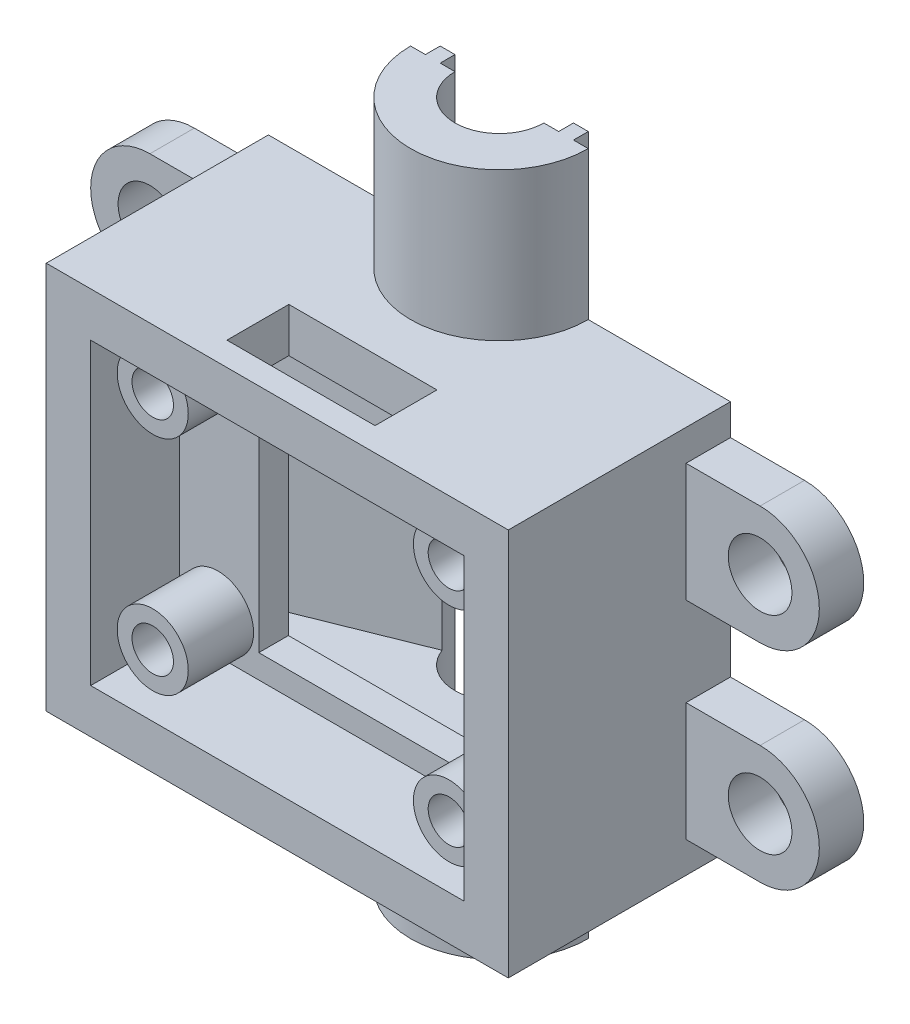
SolidWorks part; units mm, degrees
ref_plane "Front Plane" through (0, 0, 0) normal (0, 0, 1) x (1, 0, 0)
ref_plane "Top Plane" through (0, 0, 0) normal (0, 1, 0) x (1, 0, 0)
ref_plane "Right Plane" through (0, 0, 0) normal (1, 0, 0) x (0, 0, -1)
sketch "Sketch1" plane through (0, 0, 0) normal (0, 0, 1) x (1, 0, 0)
  line L1 (-15.6, -13.1) -> (15.6, -13.1)
  line L2 (-15.6, -13.1) -> (-15.6, 13.1)
  line L3 (-15.6, 13.1) -> (15.6, 13.1)
  line L4 (15.6, -13.1) -> (15.6, 13.1)
  line L5 (-15.6, -13.1) -> (15.6, 13.1) construction
  line L6 (-15.6, 13.1) -> (15.6, -13.1) construction
  point P0 (0, 0)
  dimension "D1" = 26.2
  dimension "D2" = 31.2
extrude "Boss-Extrude1" add sketch "Sketch1" along normal blind 15
shell "Shell2" thickness 3
sketch "Sketch3" plane through (0, 13.1, 0) normal (0, 1, 0) x (1, 0, 0)
  line L0 (15.6, 0) -> (-15.6, 0) construction
  line L1 (-6, 0) -> (-3, 0)
  line L2 (3, 0) -> (6, 0)
  arc A0 (-6, 0) -> (6, 0) centre (0, 0) ccw
  arc A1 (-3, 0) -> (3, 0) centre (0, 0) ccw
  dimension "D2" = 3
  dimension "D1" = 3
extrude "Boss-Extrude2" add sketch "Sketch3" along normal blind 10
ref_plane "Plane1" through (0, 0, 0) normal (0, 1, 0) x (1, 0, 0)
mirror "Mirror1" about plane through (0, 0, 0) normal (0, 1, 0) of "Boss-Extrude2"
sketch "Sketch4" plane through (0, 13.1, 0) normal (0, 1, 0) x (1, 0, 0)
  line L0 (3, 0) -> (-3, 0) construction
  line L1 (-3, 0) -> (3, 0)
  arc A0 (-3, 0) -> (3, 0) centre (0, 0) ccw
extrude "Cut-Extrude2" cut sketch "Sketch4" against normal through all
sketch "Sketch5" plane through (0, 13.1, 0) normal (0, 1, 0) x (1, 0, 0)
  line L1 (-5, -9.22) -> (5, -9.22)
  line L2 (-5, -9.22) -> (-5, -13.4)
  line L3 (-5, -13.4) -> (5, -13.4)
  line L4 (5, -9.22) -> (5, -13.4)
  line L5 (-5, -9.22) -> (5, -13.4) construction
  line L6 (-5, -13.4) -> (5, -9.22) construction
  line L9 (15.6, -15) -> (-15.6, -15) construction
  point P0 (0, -11.31)
  dimension "D1" = 10
  dimension "D3" = 4.18
  dimension "D4" = 1.6
sketch "Sketch8" plane through (0, 0, 0) normal (0, 0, -1) x (-1, 0, 0)
  line L0 (-15.6, 11) -> (-20.6, 11)
  line L1 (-15.6, -13.1) -> (-15.6, 13.1) construction
  line L2 (-15.6, 3) -> (-20.6, 3)
  line L3 (8.25, 0) -> (-8.25, 0) construction
  line L4 (-15.6, -3) -> (-20.6, -3)
  line L5 (-15.6, -11) -> (-20.6, -11)
  arc A0 (-20.6, 11) -> (-20.6, 3) centre (-20.6, 7) ccw
  circle A1 centre (-20.6, 7) radius 2.15
  circle A2 centre (-20.6, -7) radius 2.15
  arc A3 (-20.6, -11) -> (-20.6, -3) centre (-20.6, -7) cw
  line M9 (-15.6, 13.1) -> (-15.6, -13.1)
  dimension "D1" = 4.3
  dimension "D4" = 5
  dimension "D2" = 8
  dimension "D3" = 3
extrude "Boss-Extrude5" add sketch "Sketch8" against normal blind 3 contours L0 A0 L2 A1 M9 | A3 L5 L4 A2 M9
ref_plane "Plane3" through (0, 0, 0) normal (1, 0, 0) x (0, 0, -1)
mirror "Mirror3" about plane through (0, 0, 0) normal (1, 0, 0) of "Boss-Extrude5"
sketch "Sketch7" plane through (0, 0, 0) normal (0, 0, -1) x (-1, 0, 0)
  line L0 (-4.5, -23.1) -> (-4.5, -11.6) construction
  line L1 (-6, -23.1) -> (-3, -23.1) construction
  line L3 (-4.5, -11.6) -> (-14.1, -11.6) construction
  line L4 (-14.1, -11.6) -> (-14.1, 11.6) construction
  line L5 (-14.1, 11.6) -> (-4.5, 11.6) construction
  line L6 (-4.5, 11.6) -> (-4.5, 23.1) construction
  line L7 (-6, 23.1) -> (-3, 23.1) construction
  line L8 (-15.6, -13.1) -> (-15.6, -11) construction
  line L9 (-15.6, 13.1) -> (-6, 13.1) construction
  line L10 (-6, -13.1) -> (-15.6, -13.1) construction
  line L11 (-4, -23.1) -> (-4, -11.1)
  line L12 (-4, -11.1) -> (-13.6, -11.1)
  line L13 (-13.6, -11.1) -> (-13.6, 11.1)
  line L14 (-13.6, 11.1) -> (-4, 11.1)
  line L15 (-4, 11.1) -> (-4, 23.1)
  line L16 (-5, -23.1) -> (-5, -12.1)
  line L17 (-5, -12.1) -> (-14.6, -12.1)
  line L18 (-14.6, -12.1) -> (-14.6, 12.1)
  line L19 (-14.6, 12.1) -> (-5, 12.1)
  line L20 (-5, 12.1) -> (-5, 23.1)
  line L21 (-5, 23.1) -> (-4, 23.1)
  line L22 (-5, -23.1) -> (-4, -23.1)
  dimension "D1" = 1.5
  dimension "D2" = 1.5
  dimension "D3" = 1.5
  dimension "D4" = 0.5
  dimension "D5" = 0.5
extrude "Boss-Extrude4" add sketch "Sketch7" along normal blind 1
ref_plane "Plane2" through (0, 0, 0) normal (1, 0, 0) x (0, 0, -1)
mirror "Mirror2" about plane through (0, 0, 0) normal (1, 0, 0) of "Boss-Extrude4"
sketch "Sketch14" plane through (0, 0, 12) normal (0, 0, -1) x (-1, 0, 0)
  line L1 (-12.6, 10.1) -> (12.6, 10.1)
  line L2 (-12.6, 10.1) -> (-12.6, -10.1)
  line L3 (-12.6, -10.1) -> (12.6, -10.1)
  line L4 (12.6, 10.1) -> (12.6, -10.1)
  line L5 (-12.6, 10.1) -> (12.6, -10.1) construction
  line L6 (-12.6, -10.1) -> (12.6, 10.1) construction
  point P0 (0, 0)
extrude "Cut-Extrude5" cut sketch "Sketch14" against normal through all
sketch "Sketch11" plane through (0, -10.1, 0) normal (0, 1, 0) x (1, 0, 0)
  line L0 (3, 0) -> (12.6, 0)
  line L1 (3, 0) -> (12.6, 0) construction
  line L2 (12.6, 0) -> (12.6, -5.003)
  line L3 (12.6, -15) -> (12.6, 0) construction
  line L4 (12.6, -5.003) -> (2.8013, -1.0736)
  line L5 (0, -8.25) -> (0, 8.25) construction
  line L6 (-12.6, -5.003) -> (-2.8013, -1.0736)
  line L7 (-12.6, 0) -> (-12.6, -5.003)
  line L8 (-3, 0) -> (-12.6, 0)
  arc A0 (-3, 0) -> (3, 0) centre (0, 0) ccw construction
  arc A1 (2.8013, -1.0736) -> (3, 0) centre (0, 0) ccw
  arc A2 (-2.8013, -1.0736) -> (-3, 0) centre (0, 0) cw
extrude "Boss-Extrude8" add sketch "Sketch11" along normal up to next
sketch "Sketch15" plane through (0, 0, 15) normal (0, 0, 1) x (1, 0, 0)
  line L1 (-15.6, 13.1) -> (15.6, 13.1)
  line L2 (-15.6, 13.1) -> (-15.6, -13.1)
  line L3 (-15.6, -13.1) -> (15.6, -13.1)
  line L4 (15.6, 13.1) -> (15.6, -13.1)
  line L5 (-15.6, 13.1) -> (15.6, -13.1) construction
  line L6 (-15.6, -13.1) -> (15.6, 13.1) construction
  line L7 (-7.25, 8.5) -> (7.25, 8.5)
  line L8 (-7.25, 8.5) -> (-7.25, -8.5)
  line L9 (-7.25, -8.5) -> (7.25, -8.5)
  line L10 (7.25, 8.5) -> (7.25, -8.5)
  line L11 (-7.25, 8.5) -> (7.25, -8.5) construction
  line L12 (-7.25, -8.5) -> (7.25, 8.5) construction
  point P0 (0, 0)
  point P7 (0, 0)
  dimension "D1" = 14.5
  dimension "D2" = 17
extrude "Boss-Extrude9" add sketch "Sketch15" along normal blind 2 from offset 8 offset against normal yes
sketch "Sketch16" plane through (0, 0, 9) normal (0, 0, 1) x (1, 0, 0)
  line L1 (-12.6, 10.1) -> (-12.6, -10.1) construction
  line L5 (12.6, -10.1) -> (-12.6, -10.1) construction
  circle A0 centre (-10, 7.5) radius 2.4
  circle A1 centre (10, 7.5) radius 2.4
  circle A2 centre (-10, -7.5) radius 2.4
  circle A3 centre (10, -7.5) radius 2.4
  circle A4 centre (-10, 7.5) radius 1.4
  circle A5 centre (-10, -7.5) radius 1.4
  circle A6 centre (10, -7.5) radius 1.4
  circle A7 centre (10, 7.5) radius 1.4
  dimension "D1" = 2.8
  dimension "D2" = 2.8
  dimension "D3" = 2.8
  dimension "D4" = 2.8
  dimension "D5" = 1
  dimension "D6" = 1
  dimension "D7" = 1
  dimension "D8" = 1
  dimension "D9" = 20
  dimension "D10" = 2.6
  dimension "D11" = 15
  dimension "D12" = 2.6
extrude "Boss-Extrude10" add sketch "Sketch16" along normal blind 4.41
extrude "Cut-Extrude6" cut sketch "Sketch5" against normal up to next
equation "\"D2@Sketch7\"=\"D1@Sketch7\""
equation "\"D3@Sketch7\"=\"D1@Sketch7\""
equation "\"D2@Sketch16\"=\"D1@Sketch16\""
equation "\"D3@Sketch16\"=\"D1@Sketch16\""
equation "\"D4@Sketch16\"=\"D1@Sketch16\""
equation "\"D6@Sketch16\"=\"D5@Sketch16\""
equation "\"D7@Sketch16\"=\"D5@Sketch16\""
equation "\"D8@Sketch16\"=\"D5@Sketch16\""
